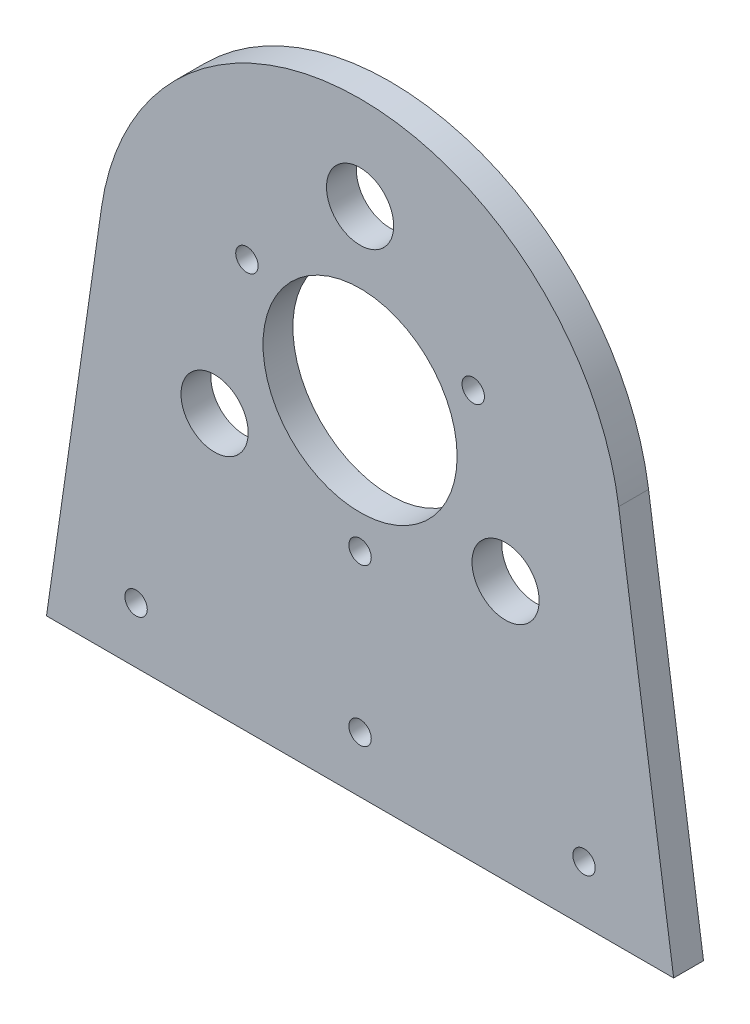
SolidWorks part; units mm, degrees
material "A-玻璃纤维"
ref_plane "前视基准面" through (0, 0, 0) normal (0, 0, 1) x (1, 0, 0)
ref_plane "上视基准面" through (0, 0, 0) normal (0, 1, 0) x (1, 0, 0)
ref_plane "右视基准面" through (0, 0, 0) normal (1, 0, 0) x (0, 0, -1)
sketch "草图1" plane through (0, 0, 0) normal (0, 0, 1) x (1, 0, 0)
  line L0 (0, 0) -> (0, -46) construction
  line L1 (0, -46) -> (42, -46)
  line L2 (0, -46) -> (-42, -46)
  line L3 (-42, -46) -> (-34.6412, 4.9985)
  line L4 (34.6412, 4.9985) -> (42, -46)
  circle A0 centre (0, 0) radius 35
  circle A1 centre (0, 0) radius 13
  point P8 (0, 0)
  dimension "D1" = 26
  dimension "D3" = 70
  dimension "D2" = 46
  dimension "D4" = 42
  dimension "D5" = 42
extrude "凸台-拉伸1" add sketch "草图1" along normal blind 4
sketch "草图2" plane through (0, 0, 4) normal (0, 0, 1) x (1, 0, 0)
  line L0 (0, 0) -> (0, 22.5) construction
  circle A0 centre (0, 22.5) radius 4.5
  circle A1 centre (19.4856, -11.25) radius 4.5
  circle A2 centre (-19.4856, -11.25) radius 4.5
  point P10 (0, 0)
  dimension "D2" = 9
  dimension "D1" = 22.5
  dimension "D3" = 3
extrude "切除-拉伸1" cut sketch "草图2" against normal through all
sketch "草图3" plane through (0, 0, 0) normal (0, 0, 1) x (1, 0, 0)
  line L0 (0, 0) -> (0, -17.5) construction
  line L1 (0, 0) -> (15.1554, 8.75) construction
  line L2 (0, 0) -> (-15.1554, 8.75) construction
  circle A0 centre (0, 0) radius 17.5 construction
  circle A1 centre (15.1554, 8.75) radius 1.5
  circle A2 centre (0, -17.5) radius 1.5
  circle A3 centre (-15.1554, 8.75) radius 1.5
  point P9 (0, 0)
  point P10 (0, 3.7607)
  dimension "D1" = 35
  dimension "D4" = 3
  dimension "D5" = 3
  dimension "D6" = 3
  dimension "D2" = 120
  dimension "D3" = 120
extrude "切除-拉伸5" cut sketch "草图3" along normal up to surface (4 mm away) up to face at (4.5, 22.5, 4)
sketch "草图4" plane through (0, 0, 4) normal (0, 0, 1) x (1, 0, 0)
  line L0 (0, -46) -> (0, 35) construction
  line L1 (42, -46) -> (-42, -46) construction
  arc A0 (34.6412, 4.9985) -> (-34.6412, 4.9985) centre (0, 0) ccw construction
  circle A1 centre (0, -38.5) radius 1.5
  circle A2 centre (-30, -38.5) radius 1.5
  circle A3 centre (30, -38.5) radius 1.5
  dimension "D1" = 3
  dimension "D2" = 7.5
  dimension "D3" = 30
extrude "切除-拉伸6" cut sketch "草图4" against normal through all
